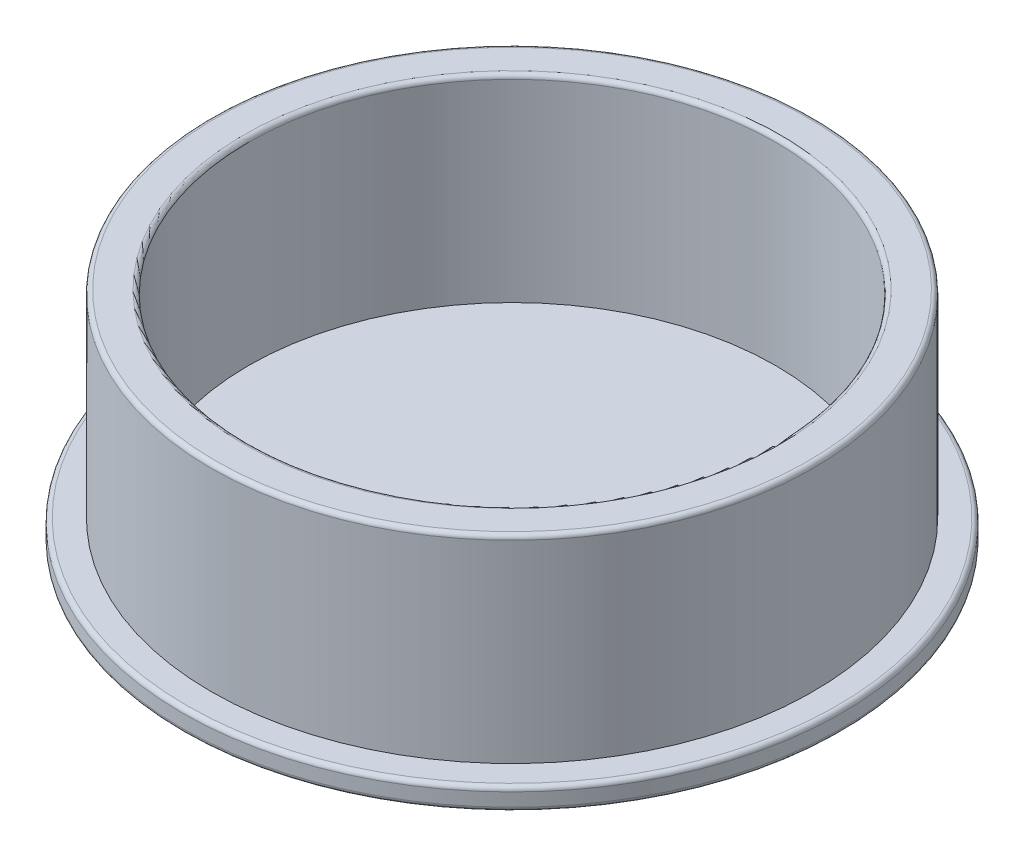
SolidWorks part; units mm, degrees
ref_plane "前视基准面" through (0, 0, 0) normal (0, 0, 1) x (1, 0, 0)
ref_plane "上视基准面" through (0, 0, 0) normal (0, 1, 0) x (1, 0, 0)
ref_plane "右视基准面" through (0, 0, 0) normal (1, 0, 0) x (0, 0, -1)
sketch "草图1" plane through (0, 0, 0) normal (0, 1, 0) x (1, 0, 0)
  circle A0 centre (0, 0) radius 15
  dimension "D1" = 30
extrude "凸台-拉伸1" add sketch "草图1" along normal blind 1
sketch "草图2" plane through (0, 1, 0) normal (0, 1, 0) x (1, 0, 0)
  circle A0 centre (0, 0) radius 13.7
  circle A1 centre (0, 0) radius 12
  dimension "D1" = 27.4
  dimension "D2" = 24
extrude "凸台-拉伸2" add sketch "草图2" along normal blind 9
fillet "圆角1" radius 0.2 4 edges at (0, 10, 12) (0, 10, 13.7) (0, 1, 15) (0, 0, 15)
